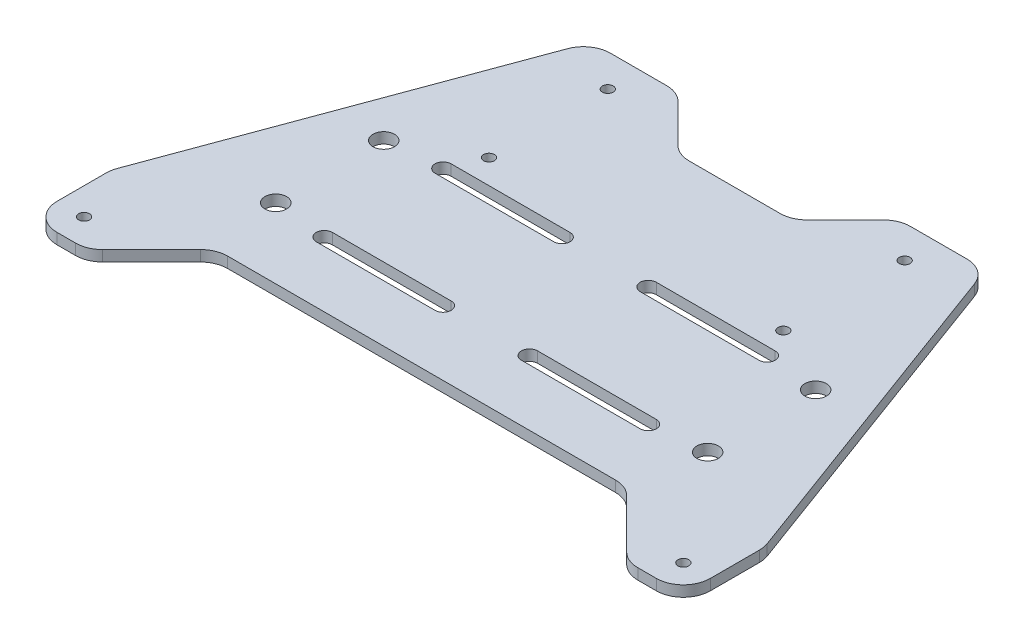
SolidWorks part; units mm, degrees
ref_plane "Front Plane" through (0, 0, 0) normal (0, 0, 1) x (1, 0, 0)
ref_plane "Top Plane" through (0, 0, 0) normal (0, 1, 0) x (1, 0, 0)
ref_plane "Right Plane" through (0, 0, 0) normal (1, 0, 0) x (0, 0, -1)
sketch "Sketch1" plane through (0, 0, 0) normal (0, 1, 0) x (1, 0, 0)
  line L1 (-8.2126, -4.5965) -> (121.7874, -4.5965)
  line L2 (-8.2126, -4.5965) -> (-8.2126, 85.4035)
  line L3 (-8.2126, 85.4035) -> (121.7874, 85.4035)
  line L4 (121.7874, -4.5965) -> (121.7874, 85.4035)
  dimension "D1" = 130
  dimension "D2" = 90
extrude "Boss-Extrude2" add sketch "Sketch1" along normal blind 2
sketch "Sketch2" plane through (0, 2, 0) normal (0, 1, 0) x (1, 0, 0)
  line L0 (121.7874, 85.4035) -> (-8.2126, 85.4035) construction
  line L1 (16.7874, 50.4035) -> (96.7874, 50.4035)
  line L2 (16.7874, 50.4035) -> (16.7874, 30.4035)
  line L3 (16.7874, 30.4035) -> (96.7874, 30.4035)
  line L4 (96.7874, 50.4035) -> (96.7874, 30.4035)
  line L5 (-8.2126, 85.4035) -> (-8.2126, -4.5965) construction
  circle A0 centre (16.7874, 50.4035) radius 2
  circle A1 centre (16.7874, 30.4035) radius 2
  circle A2 centre (96.7874, 50.4035) radius 2
  circle A3 centre (96.7874, 30.4035) radius 2
  point P6 (16.7874, 40.4035)
  point P7 (56.7874, 50.4035)
  dimension "D1" = 20
  dimension "D2" = 80
  dimension "D3" = 45
  dimension "D4" = 65
extrude "Cut-Extrude1" cut sketch "Sketch2" against normal blind 10 contours A0 | A1 | A3 | A2
sketch "Sketch4" plane through (0, 2, 0) normal (0, 1, 0) x (1, 0, 0)
  line L0 (26.7874, 51.4035) -> (48.7874, 51.4035) construction
  line L1 (26.7874, 52.9035) -> (48.7874, 52.9035)
  line L2 (26.7874, 49.9035) -> (48.7874, 49.9035)
  line L3 (26.7874, 29.4035) -> (48.7874, 29.4035) construction
  line L4 (26.7874, 30.9035) -> (48.7874, 30.9035)
  line L5 (26.7874, 27.9035) -> (48.7874, 27.9035)
  line L6 (64.7874, 51.4035) -> (86.7874, 51.4035) construction
  line L7 (64.7874, 52.9035) -> (86.7874, 52.9035)
  line L8 (64.7874, 49.9035) -> (86.7874, 49.9035)
  line L9 (64.7874, 29.4035) -> (86.7874, 29.4035) construction
  line L10 (64.7874, 30.9035) -> (86.7874, 30.9035)
  line L11 (64.7874, 27.9035) -> (86.7874, 27.9035)
  arc A0 (26.7874, 52.9035) -> (26.7874, 49.9035) centre (26.7874, 51.4035) ccw
  arc A1 (48.7874, 49.9035) -> (48.7874, 52.9035) centre (48.7874, 51.4035) ccw
  arc A2 (26.7874, 30.9035) -> (26.7874, 27.9035) centre (26.7874, 29.4035) ccw
  arc A3 (48.7874, 27.9035) -> (48.7874, 30.9035) centre (48.7874, 29.4035) ccw
  arc A4 (64.7874, 52.9035) -> (64.7874, 49.9035) centre (64.7874, 51.4035) ccw
  arc A5 (86.7874, 49.9035) -> (86.7874, 52.9035) centre (86.7874, 51.4035) ccw
  arc A6 (64.7874, 30.9035) -> (64.7874, 27.9035) centre (64.7874, 29.4035) ccw
  arc A7 (86.7874, 27.9035) -> (86.7874, 30.9035) centre (86.7874, 29.4035) ccw
  circle A8 centre (16.7874, 30.4035) radius 2 construction
  circle A10 centre (16.7874, 50.4035) radius 2 construction
  circle A12 centre (96.7874, 30.4035) radius 2 construction
  circle A14 centre (96.7874, 50.4035) radius 2 construction
  point P2 (37.7874, 51.4035)
  point P7 (37.7874, 29.4035)
  point P14 (75.7874, 51.4035)
  point P21 (75.7874, 29.4035)
  dimension "D1" = 1.5
  dimension "D2" = 1.5
  dimension "D3" = 1.5
  dimension "D5" = 1.5
  dimension "D4" = 10
  dimension "D13" = 10
  dimension "D14" = 10
  dimension "D6" = 22
  dimension "D7" = 22
  dimension "D8" = 22
  dimension "D9" = 22
  dimension "D10" = 22
  dimension "D11" = 21
  dimension "D12" = 0
extrude "Cut-Extrude3" cut sketch "Sketch4" against normal blind 10
sketch "Sketch5" plane through (0, 2, 0) normal (0, 1, 0) x (1, 0, 0)
  line L0 (-8.2126, 40.4035) -> (121.7874, 40.4035) construction
  line L1 (-8.2126, 85.4035) -> (-8.2126, -4.5965) construction
  line L2 (121.7874, -4.5965) -> (121.7874, 85.4035) construction
  line L3 (56.7874, 85.4035) -> (56.7874, -4.5965) construction
  line L4 (121.7874, 85.4035) -> (-8.2126, 85.4035) construction
  line L5 (-8.2126, -4.5965) -> (121.7874, -4.5965) construction
  line L6 (-3.2126, 57.4035) -> (29.2874, 57.4035)
  line L7 (84.2874, 57.4035) -> (116.7874, 57.4035)
  line L8 (84.2874, 57.4035) -> (84.2874, 79.4035)
  line L9 (84.2874, 79.4035) -> (116.7874, 79.4035)
  line L10 (116.7874, 57.4035) -> (116.7874, 79.4035)
  line L11 (-3.2126, 57.4035) -> (-3.2126, 79.4035)
  line L12 (-3.2126, 79.4035) -> (29.2874, 79.4035)
  line L13 (29.2874, 57.4035) -> (29.2874, 79.4035)
  circle A0 centre (1.2874, 10.4035) radius 1
  circle A1 centre (112.2874, 10.4035) radius 1
  circle A2 centre (84.2874, 56.9208) radius 1
  circle A3 centre (116.7874, 57.4035) radius 1
  circle A4 centre (116.7874, 79.4035) radius 1
  circle A5 centre (84.2874, 79.4035) radius 1
  circle A6 centre (-3.2126, 57.4035) radius 1
  circle A7 centre (29.2874, 57.4035) radius 1
  circle A8 centre (29.2874, 79.4035) radius 1
  circle A9 centre (-3.2126, 79.4035) radius 1
  point P29 (0, 0)
  point P34 (0, 0)
  point P35 (0, 0)
  dimension "D3" = 2
  dimension "D4" = 2
  dimension "D5" = 111
  dimension "D6" = 55.5
  dimension "D11" = 27.5
  dimension "D1" = 30
  dimension "D2" = 0
  dimension "D7" = 22
  dimension "D8" = 32.5
  dimension "D9" = 39
  dimension "D10" = 27.5
  dimension "D12" = 39
extrude "Cut-Extrude4" cut sketch "Sketch5" against normal blind 10 contours A0 | A1 | A2 | A3 | A4 | A5 | A8 | A7 | A6 | A9
sketch "Sketch7" plane through (0, 2, 0) normal (0, 1, 0) x (1, 0, 0)
  line L0 (121.7874, -4.5965) -> (121.7874, 85.4035) construction
  line L1 (-8.2126, -4.5965) -> (121.7874, -4.5965)
  line L2 (-8.2126, -4.5965) -> (-8.2126, 5.4035)
  line L3 (-8.2126, 5.4035) -> (121.7874, 5.4035)
  line L4 (121.7874, -4.5965) -> (121.7874, 5.4035)
  line L5 (121.7874, 85.4035) -> (-8.2126, 85.4035) construction
  dimension "D1" = 80
extrude "Cut-Extrude5" cut sketch "Sketch7" against normal blind 10
sketch "Sketch9" plane through (0, 2, 0) normal (0, 1, 0) x (1, 0, 0)
  line L0 (6.7874, 5.4035) -> (18.7874, 17.4035)
  line L1 (121.7874, 5.4035) -> (-8.2126, 5.4035) construction
  line L2 (18.7874, 17.4035) -> (94.7874, 17.4035)
  line L3 (94.7874, 17.4035) -> (106.7874, 5.4035)
  line L4 (-8.2126, 85.4035) -> (-8.2126, 5.4035) construction
  line L5 (121.7874, 5.4035) -> (121.7874, 85.4035) construction
  dimension "D1" = 15
  dimension "D2" = 15
  dimension "D3" = 12
  dimension "D4" = 45
extrude "Cut-Extrude10" cut sketch "Sketch9" along direction (0, -1, 0) on the side against the normal through all and the other way through all flip side to cut
sketch "Sketch12" plane through (0, 2, 0) normal (0, 1, 0) x (1, 0, 0)
  line L0 (6.7874, 5.4035) -> (-8.2126, 5.4035) construction
  line L1 (-3.7126, 5.4035) -> (-3.7126, 20.4035)
  line L2 (-3.7126, 20.4035) -> (20.2874, 85.4035)
  line L3 (121.7874, 85.4035) -> (-8.2126, 85.4035) construction
  line L4 (20.2874, 85.4035) -> (36.2874, 85.4035)
  line L5 (36.2874, 85.4035) -> (46.2874, 75.4035)
  line L6 (46.2874, 75.4035) -> (67.2874, 75.4035)
  line L7 (67.2874, 75.4035) -> (77.2874, 85.4035)
  line L8 (77.2874, 85.4035) -> (93.2874, 85.4035)
  line L9 (93.2874, 85.4035) -> (117.2874, 20.4035)
  line L10 (117.2874, 20.4035) -> (117.2874, 5.4035)
  line L11 (121.7874, 5.4035) -> (106.7874, 5.4035) construction
  circle A1 centre (1.2874, 10.4035) radius 1 construction
  circle A2 centre (112.2874, 10.4035) radius 1 construction
  circle M9 centre (-3.2126, 57.4035) radius 1
  circle M10 centre (-3.2126, 79.4035) radius 1
  circle M11 centre (116.7874, 79.4035) radius 1
  circle M12 centre (116.7874, 57.4035) radius 1
  line M36 (-8.2126, 5.4035) -> (6.7874, 5.4035)
  line M40 (106.7874, 5.4035) -> (121.7874, 5.4035)
  line M41 (121.7874, 5.4035) -> (121.7874, 85.4035)
  line M42 (121.7874, 85.4035) -> (-8.2126, 85.4035)
  line M43 (-8.2126, 85.4035) -> (-8.2126, 5.4035)
  dimension "D1" = 5
  dimension "D2" = 5
  dimension "D3" = 15
  dimension "D4" = 15
  dimension "D5" = 24
  dimension "D6" = 24
  dimension "D7" = 16
  dimension "D8" = 16
  dimension "D9" = 10
  dimension "D10" = 45
extrude "Cut-Extrude14" cut sketch "Sketch12" against normal blind 13 and the other way through all contours L1 L2 M42 M43 M36 M10 M9 | L6 L7 L5 M42 | L9 L10 M40 M41 M42 M12 M11
fillet "Fillet2" radius 5 14 edges at (-3.7126, 1, -5.4035) (18.7874, 1, -17.4035) (6.7874, 1, -5.4035) (94.7874, 1, -17.4035) (106.7874, 1, -5.4035) (117.2874, 1, -5.4035) (93.2874, 1, -85.4035) (20.2874, 1, -85.4035) (36.2874, 1, -85.4035) (46.2874, 1, -75.4035) (67.2874, 1, -75.4035) (77.2874, 1, -85.4035)
